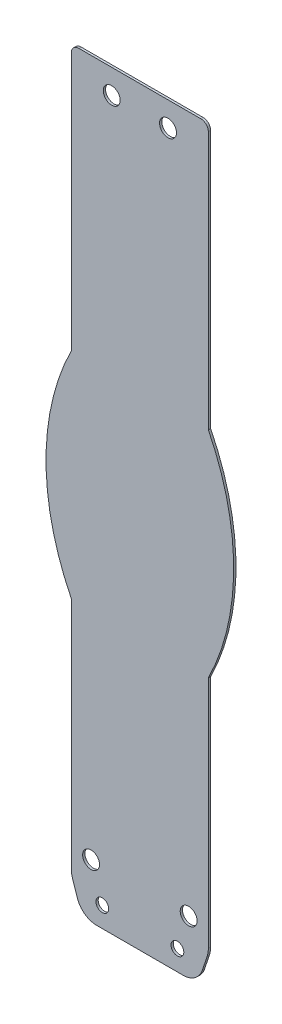
SolidWorks part; units mm, degrees
ref_plane "Front Plane" through (0, 0, 0) normal (0, 0, 1) x (1, 0, 0)
ref_plane "Top Plane" through (0, 0, 0) normal (0, 1, 0) x (1, 0, 0)
ref_plane "Right Plane" through (0, 0, 0) normal (1, 0, 0) x (0, 0, -1)
sketch "Sketch2" plane through (0, 0, 0) normal (0, 0, 1) x (1, 0, 0)
  line L0 (34.8835, 3.6866) -> (36.1641, 7.5139)
  line L1 (6.7374, 0) -> (29.7626, 0)
  line L2 (0, 9.5763) -> (0, 198)
  line L3 (2, 200) -> (34.5, 200)
  line L4 (36.5, 9.5763) -> (36.5, 198)
  line L5 (1.6165, 3.6866) -> (0.3359, 7.5139)
  arc A0 (34.8835, 3.6866) -> (29.7626, 0) centre (29.7626, 5.4) cw
  arc A1 (1.6165, 3.6866) -> (6.7374, 0) centre (6.7374, 5.4) ccw
  arc A2 (36.1641, 7.5139) -> (36.5, 9.5763) centre (30, 9.5763) ccw
  arc A3 (0.3359, 7.5139) -> (0, 9.5763) centre (6.5, 9.5763) cw
  arc A4 (34.5, 200) -> (36.5, 198) centre (34.5, 198) cw
  arc A5 (0, 198) -> (2, 200) centre (2, 198) cw
  point P11 (33.65, 0)
  point P14 (2.85, 0)
  point P17 (36.5, 8.5178)
  point P20 (0, 8.5178)
  dimension "D6" = 5.4
  dimension "D7" = 6.5
  dimension "D1" = 36.5
  dimension "D2" = 200
  dimension "D3" = 71.5
  dimension "D4" = 71.5
  dimension "D5" = 30.8
extrude "Boss-Extrude1" add sketch "Sketch2" along normal blind 0.6096
sketch "Sketch3" plane through (0, 0, 0.6096) normal (0, 0, 1) x (1, 0, 0)
  line L3 (18.25, 0) -> (18.25, 200) construction
  line L4 (6.7374, 0) -> (29.7626, 0) construction
  line L5 (34.5, 200) -> (2, 200) construction
  circle A0 centre (8.25, 5.4) radius 1.7
  circle A1 centre (5.25, 14.4) radius 2.25
  circle A3 centre (10.75, 193.5) radius 2.25
  circle A4 centre (28.25, 5.4) radius 1.7
  circle A5 centre (31.25, 14.4) radius 2.25
  circle A6 centre (25.75, 193.5) radius 2.25
  point P7 (3, 14.4)
  dimension "D1" = 3.4
  dimension "D3" = 4.5
  dimension "D7" = 4.5
  dimension "D2" = 10
  dimension "D4" = 3
  dimension "D5" = 9
  dimension "D6" = 5.4
  dimension "D8" = 6.5
  dimension "D9" = 7.5
extrude "Cut-Extrude1" cut sketch "Sketch3" against normal through all
sketch "Sketch4" plane through (0, 0, 0.6096) normal (0, 0, 1) x (1, 0, 0)
  line L0 (0, 198) -> (0, 9.5763) construction
  line L1 (36.5, 9.5763) -> (36.5, 198) construction
  line L2 (6.7374, 0) -> (29.7626, 0) construction
  line L3 (18.25, 0) -> (18.25, 200) construction
  line L4 (34.5, 200) -> (2, 200) construction
  line L5 (0, 72) -> (36.5, 72)
  line L6 (0, 129.225) -> (36.5, 129.225)
  line L7 (18.25, 129.225) -> (18.25, 72)
  arc A0 (0, 72) -> (0, 129.225) centre (57.2676, 100.6125) cw
  arc A1 (36.5, 72) -> (36.5, 129.225) centre (-20.7676, 100.6125) ccw
  point P0 (0, 72)
  point P1 (36.5, 72)
  point P15 (43.25, 100.6125)
  point P22 (-6.75, 100.6125)
  line M16 (36.5, 9.5763) -> (36.5, 198)
  line M20 (0, 198) -> (0, 9.5763)
  dimension "D1" = 72
  dimension "D2" = 25
  dimension "D3" = 57.225
extrude "Boss-Extrude2" add sketch "Sketch4" against normal up to surface (0.6096 mm away) contours L7 L6 L5 M20 | A0 M20 | L6 L7 L5 M16 | A1 M16 up to face at (7.5, 14.4, 0)
